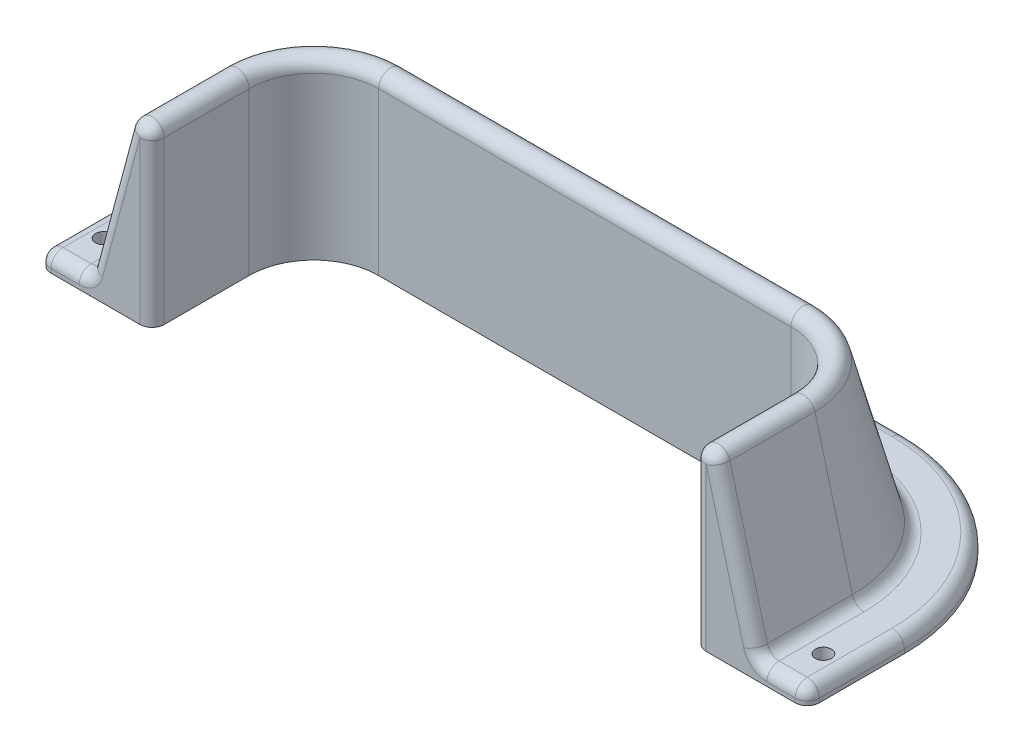
SolidWorks part; units mm, degrees
material "ABS"
ref_plane "Plan de face" through (0, 0, 0) normal (0, 0, 1) x (1, 0, 0)
ref_plane "Plan de dessus" through (0, 0, 0) normal (0, 1, 0) x (1, 0, 0)
ref_plane "Plan de droite" through (0, 0, 0) normal (1, 0, 0) x (0, 0, -1)
sketch "Esquisse1" plane through (0, 0, 0) normal (0, 1, 0) x (1, 0, 0)
  line L1 (-33.5, 0) -> (33.5, 0) construction
  line L2 (-33.5, 0) -> (-33.5, 12)
  line L3 (-25.5, 20) -> (25.5, 20)
  line L4 (33.5, 0) -> (33.5, 12)
  arc A0 (25.5, 20) -> (33.5, 12) centre (25.5, 12) cw
  arc A1 (-33.5, 12) -> (-25.5, 20) centre (-25.5, 12) cw
  dimension "D3" = 8
  dimension "D1" = 20
  dimension "D2" = 67
sketch "Esquisse2" plane through (0, 0, 0) normal (0, 0, 1) x (1, 0, 0)
  line L0 (-33.5, 0) -> (-33.5, 20)
  line L2 (-36.4489, 20.3882) -> (-41.0781, 3.1118)
  line L3 (-42.527, 2) -> (-47.5, 2)
  line L4 (-47.5, 2) -> (-47.5, 0)
  line L5 (-47.5, 0) -> (-33.5, 0)
  arc A0 (-33.5, 20) -> (-36.4489, 20.3882) centre (-35, 20) ccw
  arc A1 (-41.0781, 3.1118) -> (-42.527, 2) centre (-42.527, 3.5) cw
  dimension "D1" = 15
  dimension "D2" = 20
  dimension "D3" = 1.5
  dimension "D4" = 2
  dimension "D5" = 14
sweep "Balayage1" add profiles "Esquisse2" path "Esquisse1"
fillet "Congé1" radius 1.5 17 edges at (33.5, 10, 0) (34.8042, 21.4872, 0) (38.7635, 11.75, 0) (41.6138, 2.31, 0) (47.5, 2, -6) (41.0563, 2, -27.5563) (0, 2, -34) (-41.0563, 2, -27.5563) (-33.5, 10, 0) (-34.8042, 21.4872, 0) (-38.7635, 11.75, 0) (-41.6138, 2.31, 0) (47.5, 1, 0) (45.0135, 2, 0) (-47.5, 2, -6) (-45.0135, 2, 0) (-47.5, 1, 0)
sketch "Esquisse3" plane through (0, 2, 0) normal (0, 1, 0) x (1, 0, 0)
  line L0 (-33.5, 12) -> (-33.5, 1.5) construction
  line L1 (-25.5, 20) -> (25.5, 20) construction
  line L2 (-46, 0) -> (-35, 0) construction
  line L3 (0, 0) -> (0, 20) construction
  circle A0 centre (-44.5, 5) radius 1
  circle A1 centre (-18.5, 31) radius 1
  circle A2 centre (44.5, 5) radius 1
  circle A3 centre (18.5, 31) radius 1
  dimension "D1" = 11
  dimension "D2" = 11
  dimension "D3" = 5
  dimension "D4" = 2
  dimension "D5" = 37
  dimension "D6" = 26
  dimension "D7" = 26
extrude "Enlèv. mat.-Extru.1" cut sketch "Esquisse3" against normal through all
